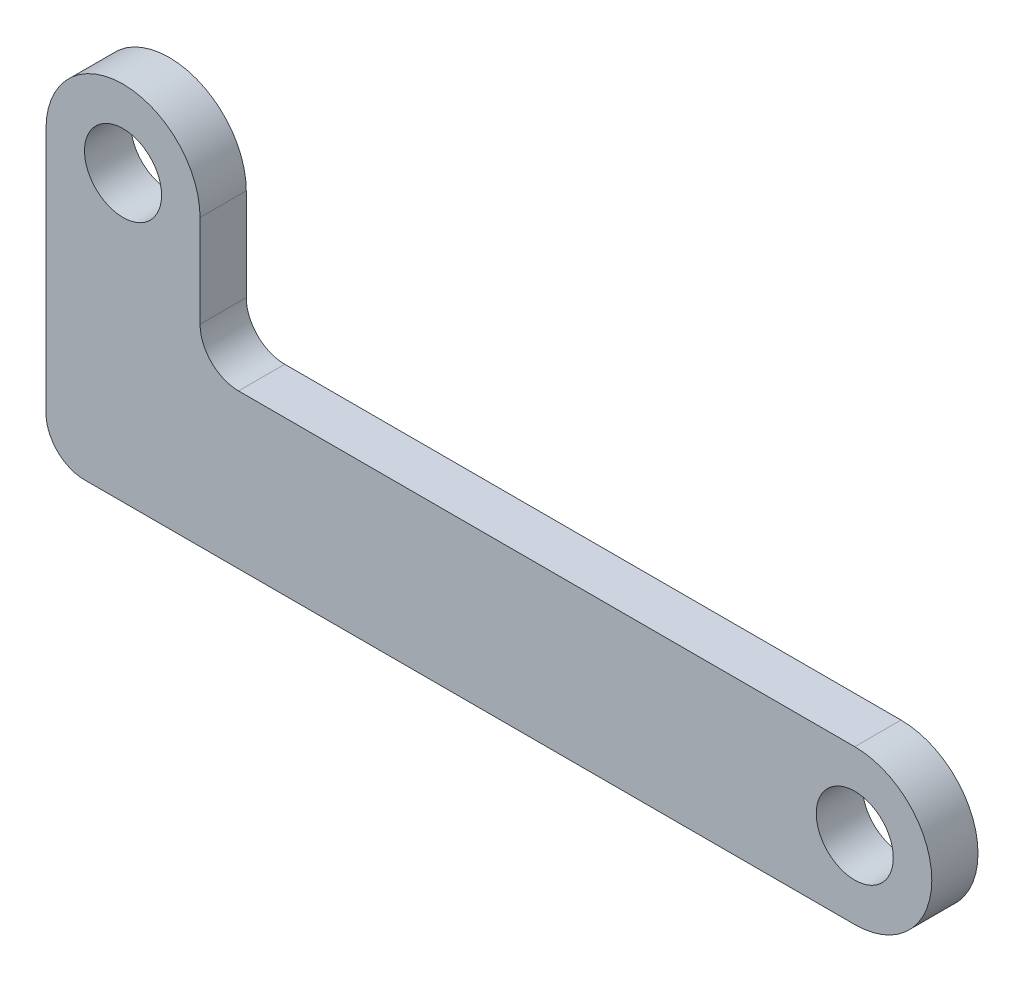
SolidWorks part; units mm, degrees
ref_plane "Спереди" through (0, 0, 0) normal (0, 0, 1) x (1, 0, 0)
ref_plane "Сверху" through (0, 0, 0) normal (0, 1, 0) x (1, 0, 0)
ref_plane "Справа" through (0, 0, 0) normal (1, 0, 0) x (0, 0, -1)
sketch "Эскиз2" plane through (0, 0, 0) normal (0, 0, 1) x (1, 0, 0)
  line L0 (40, 0) -> (-10, 0) construction
  line L1 (5, 0) -> (5, -6)
  line L2 (-5, 0) -> (-5, -16)
  line L3 (7.5, -8.5) -> (47.5, -8.5)
  line L6 (-2.5, -18.5) -> (47.5, -18.5)
  circle A0 centre (0, 0) radius 2.5
  arc A1 (5, 0) -> (-5, 0) centre (0, 0) ccw
  arc A2 (47.5, -8.5) -> (47.5, -18.5) centre (47.5, -13.5) cw
  arc A3 (-5, -16) -> (-2.5, -18.5) centre (-2.5, -16) ccw
  arc A4 (5, -6) -> (7.5, -8.5) centre (7.5, -6) ccw
  circle A5 centre (47.5, -13.5) radius 2.5
  point P15 (0, 0)
  dimension "D1" = 5
  dimension "D3" = 2.5
  dimension "D5" = 5
  dimension "D6" = 16
  dimension "D7" = 40
  dimension "D2" = 5
  dimension "D4" = 2.5
  dimension "D8" = 5
extrude "Вытянуть1" add sketch "Эскиз2" along normal blind 3
